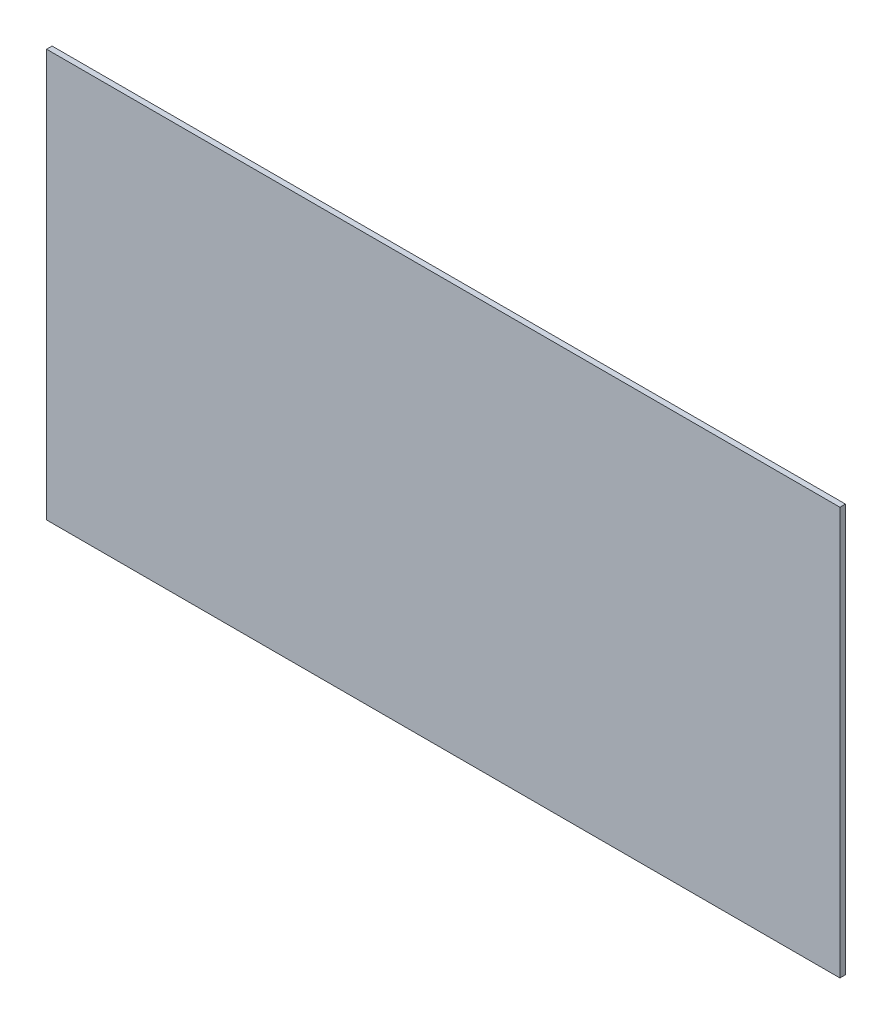
SolidWorks part; units mm, degrees
material "Pine"
ref_plane "Front Plane" through (0, 0, 0) normal (0, 0, 1) x (1, 0, 0)
ref_plane "Top Plane" through (0, 0, 0) normal (0, 1, 0) x (1, 0, 0)
ref_plane "Right Plane" through (0, 0, 0) normal (1, 0, 0) x (0, 0, -1)
sketch "Sketch1" plane through (0, 0, 0) normal (0, 0, 1) x (1, 0, 0)
  line L1 (-914.4, -469.9) -> (914.4, -469.9)
  line L2 (-914.4, -469.9) -> (-914.4, 469.9)
  line L3 (-914.4, 469.9) -> (914.4, 469.9)
  line L4 (914.4, -469.9) -> (914.4, 469.9)
  line L5 (-914.4, -469.9) -> (914.4, 469.9) construction
  line L6 (-914.4, 469.9) -> (914.4, -469.9) construction
  point P0 (0, 0)
  dimension "D1" = 1828.8
  dimension "D2" = 939.8
extrude "Boss-Extrude1" add sketch "Sketch1" along normal mid plane 12.7 contours L3 L4 L1 L2
